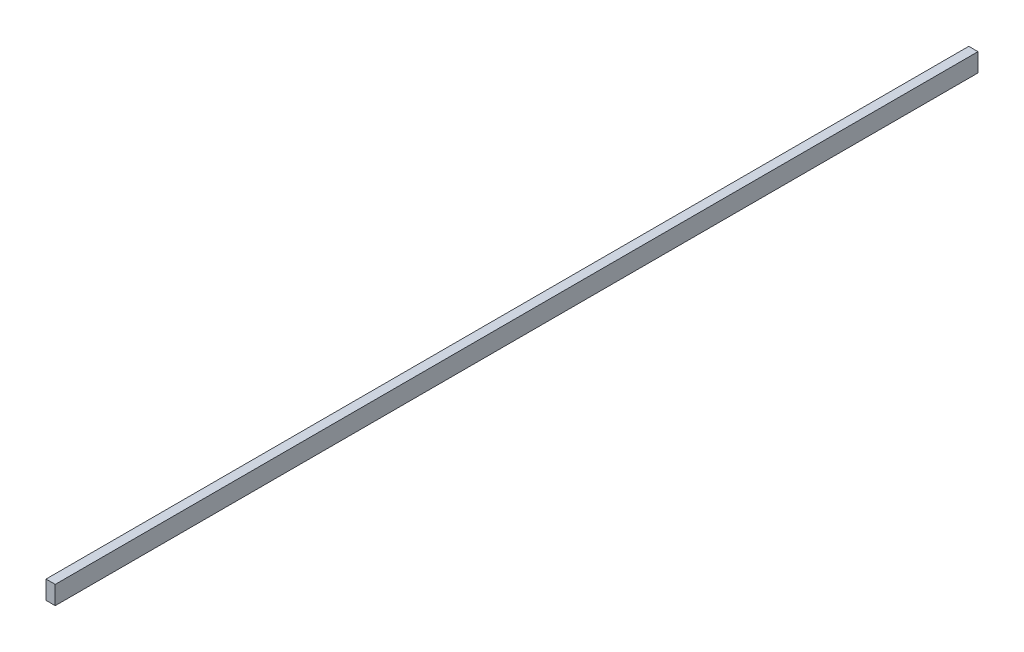
SolidWorks part; units mm, degrees
material "Acrylic (Medium-high impact)"
ref_plane "Front Plane" through (0, 0, 0) normal (0, 0, 1) x (1, 0, 0)
ref_plane "Top Plane" through (0, 0, 0) normal (0, 1, 0) x (1, 0, 0)
ref_plane "Right Plane" through (0, 0, 0) normal (1, 0, 0) x (0, 0, -1)
sketch "Sketch1" plane through (0, 0, 0) normal (0, 0, 1) x (1, 0, 0)
  line L0 (0, 10) -> (0, 0)
  line L1 (0, 0) -> (5, 0)
  line L10 (5, 5) -> (5, 10)
  line L11 (5, 10) -> (0, 10)
  line L12 (5, 5) -> (5, 0)
  dimension "D2" = 10
  dimension "D4" = 5
extrude "Boss-Extrude1" add sketch "Sketch1" along normal blind 500
